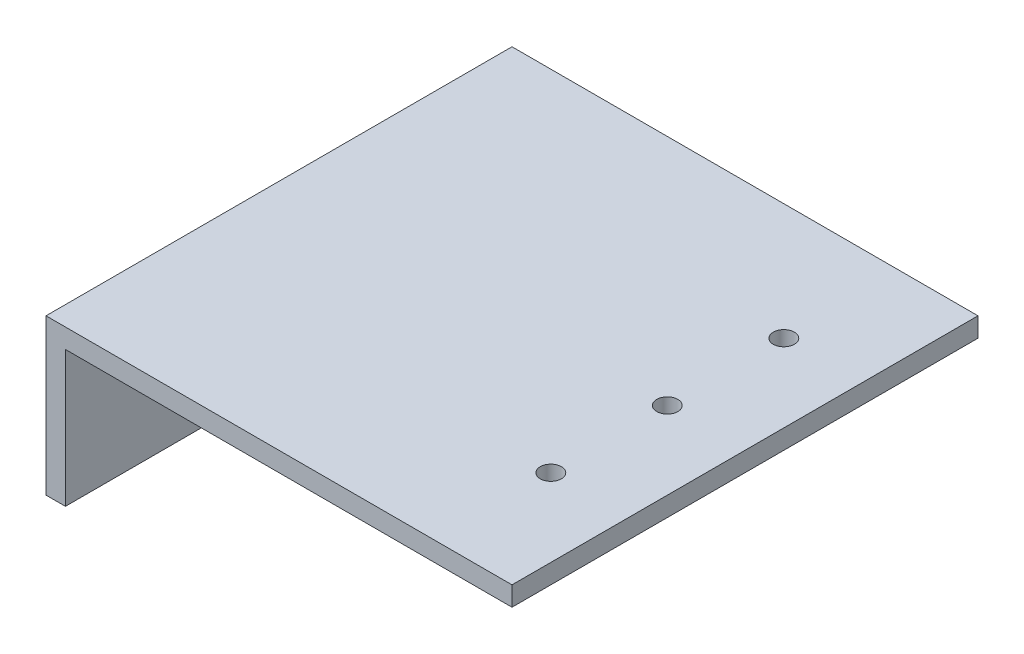
SolidWorks part; units mm, degrees
ref_plane "Front Plane" through (0, 0, 0) normal (0, 0, 1) x (1, 0, 0)
ref_plane "Top Plane" through (0, 0, 0) normal (0, 1, 0) x (1, 0, 0)
ref_plane "Right Plane" through (0, 0, 0) normal (1, 0, 0) x (0, 0, -1)
sketch "Sketch2" plane through (0, 0, 0) normal (0, 0, 1) x (1, 0, 0)
  line L0 (0, 0) -> (-76.2, 0)
  line L1 (-76.2, 0) -> (-76.2, -25.4)
  line L2 (-76.2, -25.4) -> (-73.025, -25.4)
  line L3 (-73.025, -25.4) -> (-73.025, -3.175)
  line L4 (-73.025, -3.175) -> (0, -3.175)
  line L5 (0, -3.175) -> (0, 0)
  dimension "D1" = 76.2
  dimension "D2" = 25.4
  dimension "D3" = 3.175
  dimension "D4" = 3.175
extrude "Boss-Extrude1" add sketch "Sketch2" along normal blind 76.2
sketch "Sketch8" plane through (-76.2, 0, 0) normal (-1, 0, 0) x (0, 0, 1)
  line L1 (76.2, 0) -> (76.2, -25.4) construction
  line L2 (76.2, -15.24) -> (38.1, -15.24) construction
  circle A0 centre (38.1, -15.24) radius 3.175
  dimension "D1" = 38.1
extrude "Cut-Extrude1" cut sketch "Sketch8" against normal up to next
hole_wizard "Tap Drill for #8-32 Tap1" positions "Sketch10" profile "Sketch9" hole size "#8-32" standard "ANSI Inch" end condition up to next
sketch "Sketch10" plane through (0, 0, 0) normal (0, 1, 0) x (1, 0, 0)
  line L0 (0, 0) -> (-76.2, 0) construction
  line L1 (0, -76.2) -> (0, 0) construction
  point P0 (-12.7, -38.1)
  point P2 (-12.7, -19.05)
  point P4 (-12.7, -57.15)
  dimension "D1" = 19.05
  dimension "D2" = 19.05
  dimension "D3" = 19.05
  dimension "D4" = 12.7
sketch "Sketch9" plane through (-12.7, 0, 38.1) normal (1, 0, 0) x (0, 0, 1)
  line L0 (0, 0) -> (0, 3.175)
  line L1 (0, 3.175) -> (1.7272, 3.175)
  line L2 (1.7272, 3.175) -> (1.7272, 0)
  line L5 (1.7272, 0) -> (0, 0)
  line L11 (0, -6.35) -> (0, 107.95) construction
  dimension "Thru Hole Dia." = 3.4544
  dimension "Thru Hole Depth" = 3.175
hole_wizard "Tap Drill for #8-32 Tap2" positions "Sketch12" profile "Sketch11" hole size "#8-32" standard "ANSI Inch" end condition up to next
sketch "Sketch12" plane through (-76.2, 0, 0) normal (-1, 0, 0) x (0, 0, 1)
  line L2 (38.1, -15.24) -> (25.4, -15.24) construction
  point P0 (25.4, -15.24)
  point P2 (50.8, -15.24)
  dimension "D1" = 12.7
  dimension "D2" = 25.4
sketch "Sketch11" plane through (-76.2, -15.24, 25.4) normal (0, 1, 0) x (0, 0, 1)
  line L0 (0, 0) -> (0, 3.175)
  line L1 (0, 3.175) -> (1.7272, 3.175)
  line L2 (1.7272, 3.175) -> (1.7272, 0)
  line L5 (1.7272, 0) -> (0, 0)
  line L11 (0, -6.35) -> (0, 107.95) construction
  dimension "Thru Hole Dia." = 3.4544
  dimension "Thru Hole Depth" = 3.175
